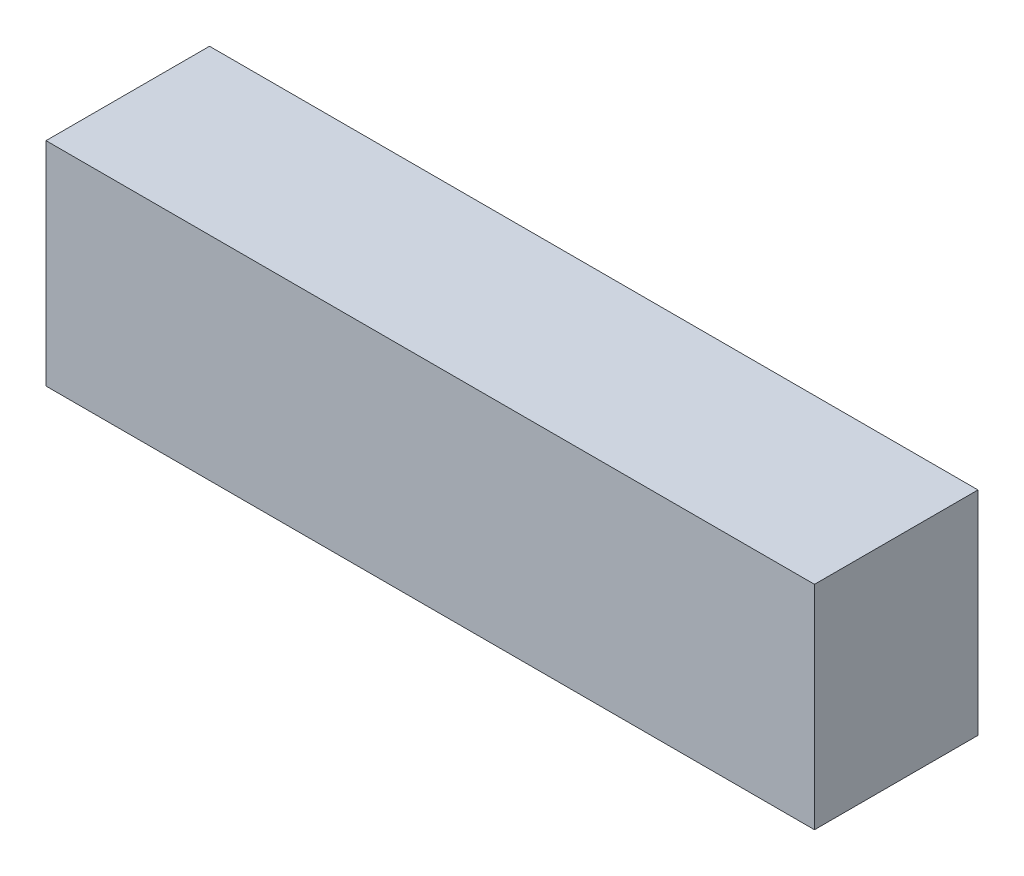
SolidWorks part; units mm, degrees
ref_plane "Front Plane" through (0, 0, 0) normal (0, 0, 1) x (1, 0, 0)
ref_plane "Top Plane" through (0, 0, 0) normal (0, 1, 0) x (1, 0, 0)
ref_plane "Right Plane" through (0, 0, 0) normal (1, 0, 0) x (0, 0, -1)
sketch "Sketch1" plane through (0, 0, 0) normal (0, 1, 0) x (1, 0, 0)
  line L1 (-59.69, -12.7) -> (59.69, -12.7)
  line L2 (-59.69, -12.7) -> (-59.69, 12.7)
  line L3 (-59.69, 12.7) -> (59.69, 12.7)
  line L4 (59.69, -12.7) -> (59.69, 12.7)
  line L5 (-59.69, -12.7) -> (59.69, 12.7) construction
  line L6 (-59.69, 12.7) -> (59.69, -12.7) construction
  point P0 (0, 0)
  dimension "D1" = 25.4
  dimension "D2" = 119.38
extrude "Boss-Extrude1" add sketch "Sketch1" along normal blind 33.02
